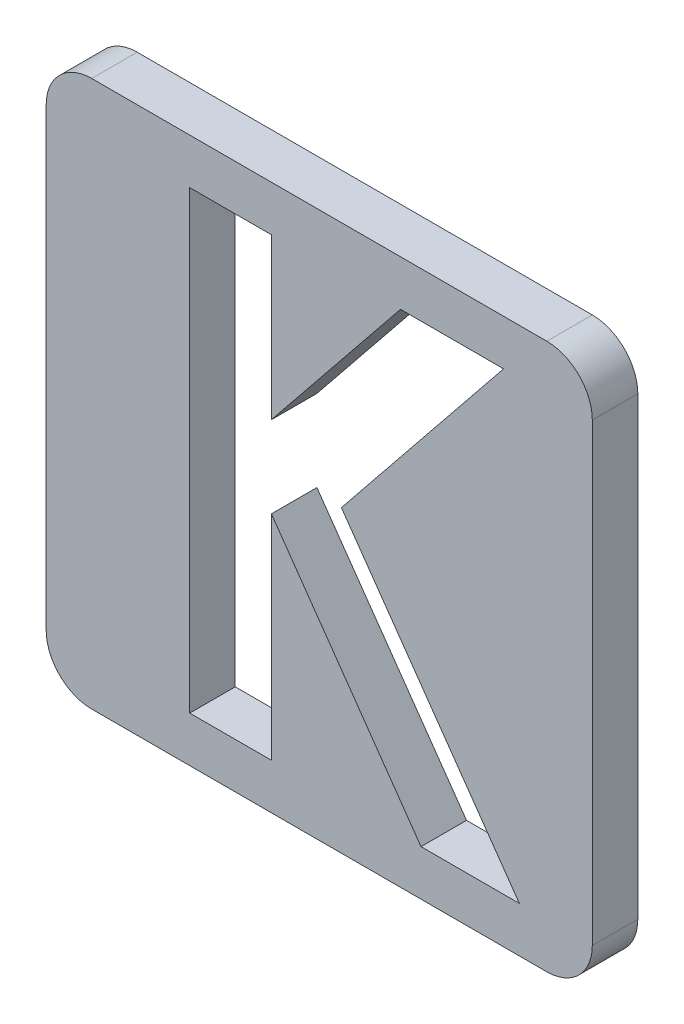
SolidWorks part; units mm, degrees
ref_plane "Front Plane" through (0, 0, 0) normal (0, 0, 1) x (1, 0, 0)
ref_plane "Top Plane" through (0, 0, 0) normal (0, 1, 0) x (1, 0, 0)
ref_plane "Right Plane" through (0, 0, 0) normal (1, 0, 0) x (0, 0, -1)
sketch "Sketch1" plane through (0, 0, 0) normal (0, 0, 1) x (1, 0, 0)
  line L1 (-50, 60) -> (50, 60)
  line L2 (-60, 50) -> (-60, -50)
  line L3 (-50, -60) -> (50, -60)
  line L4 (60, 50) -> (60, -50)
  line L5 (-60, 60) -> (60, -60) construction
  line L6 (-60, -60) -> (60, 60) construction
  arc A0 (-60, -50) -> (-50, -60) centre (-50, -50) ccw
  arc A1 (50, -60) -> (60, -50) centre (50, -50) ccw
  arc A2 (50, 60) -> (60, 50) centre (50, 50) cw
  arc A3 (-50, 60) -> (-60, 50) centre (-50, 50) ccw
  point P0 (0, 0)
  dimension "D3" = 10
  dimension "D1" = 120
  dimension "D2" = 120
extrude "Boss-Extrude1" add sketch "Sketch1" along normal blind 10 contours A3 L2 A0 L3 A1 L4 A2 L1
sketch "Sketch2" plane through (0, 0, 10) normal (0, 0, 1) x (1, 0, 0)
  line L0 (0, 0) -> (0, 40) construction
  line L1 (-50, 50) -> (50, 50) construction
  line L2 (-50, 50) -> (-50, -50) construction
  line L3 (-50, -50) -> (50, -50) construction
  line L4 (50, 50) -> (50, -50) construction
  line L5 (-50, 50) -> (50, -50) construction
  line L6 (-50, -50) -> (50, 50) construction
  line L7 (0, 40) -> (-40, 40) construction
  line L8 (-40, 40) -> (-40, 0) construction
  line L9 (-40, 0) -> (0, 0) construction
  line L11 (0, 20) -> (-20, 20) construction
  line L12 (-20, 40) -> (-20, 20) construction
  circle A0 centre (0, 40) radius 4 construction
  circle A1 centre (0, 20) radius 4 construction
  circle A2 centre (0, 0) radius 4 construction
  circle A3 centre (-20, 20) radius 4 construction
  circle A4 centre (-20, 40) radius 4 construction
  circle A5 centre (-40, 40) radius 4 construction
  circle A6 centre (0, 0) radius 4 construction
  circle A7 centre (20, 0) radius 4 construction
  circle A8 centre (40, 0) radius 4 construction
  circle A9 centre (40, 20) radius 4 construction
  circle A10 centre (40, 40) radius 4 construction
  circle A11 centre (20, 20) radius 4 construction
  circle A12 centre (0, 0) radius 4 construction
  circle A13 centre (0, -20) radius 4 construction
  circle A14 centre (0, -40) radius 4 construction
  circle A15 centre (20, -40) radius 4 construction
  circle A16 centre (40, -40) radius 4 construction
  circle A17 centre (20, -20) radius 4 construction
  circle A18 centre (0, 0) radius 4 construction
  circle A19 centre (-20, 0) radius 4 construction
  circle A20 centre (-40, 0) radius 4 construction
  circle A21 centre (-40, -20) radius 4 construction
  circle A22 centre (-40, -40) radius 4 construction
  circle A23 centre (-20, -20) radius 4 construction
  text T0 "K" font "Century Gothic" height 100
  point P0 (0, 0)
  point P55 (0, 0)
  dimension "D4" = 8
  dimension "D1" = 100
  dimension "D2" = 100
  dimension "D3" = 40
  dimension "D5" = 4
extrude "Cut-Extrude24" cut sketch "Sketch2" against normal blind 10
